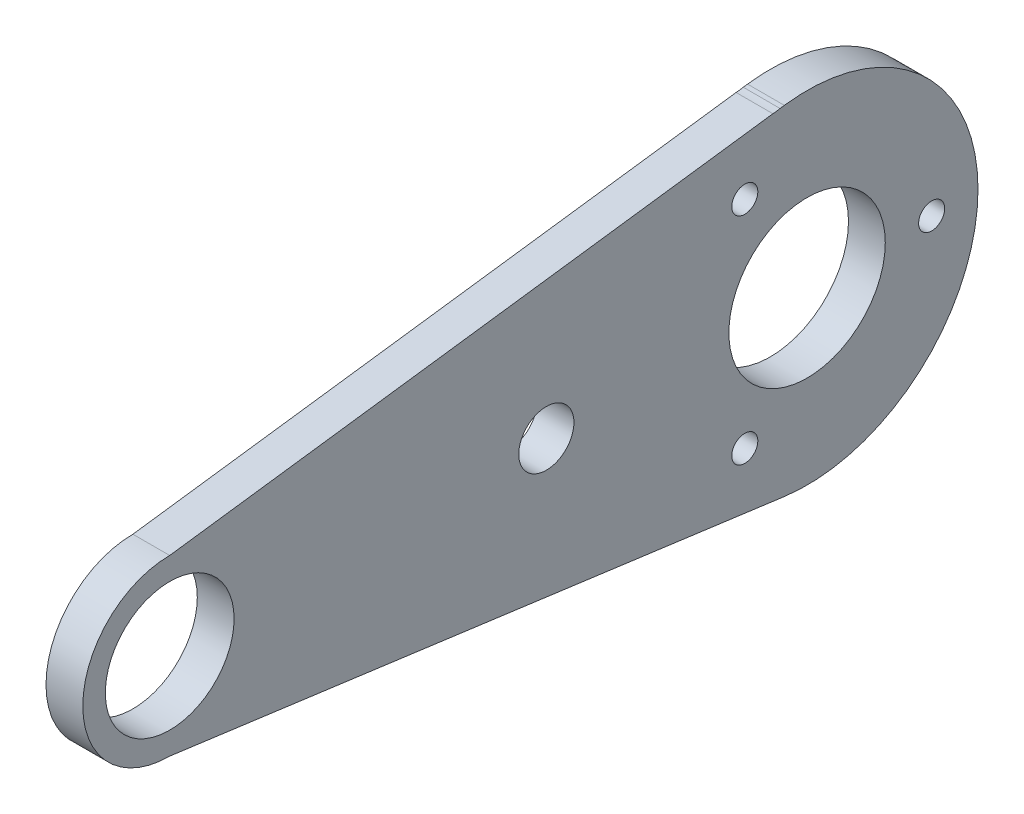
SolidWorks part; units mm, degrees
ref_plane "Front Plane" through (0, 0, 0) normal (0, 0, 1) x (1, 0, 0)
ref_plane "Top Plane" through (0, 0, 0) normal (0, 1, 0) x (1, 0, 0)
ref_plane "Right Plane" through (0, 0, 0) normal (1, 0, 0) x (0, 0, -1)
sketch "Sketch1" plane through (0, 0, 0) normal (1, 0, 0) x (0, 0, -1)
  line L4 (0, 15) -> (0, 11.1125) construction
  line L6 (0, 11.1125) -> (0, -11.1125) construction
  line L7 (0, -11.1125) -> (0, -15) construction
  line L8 (0, 15) -> (106.0756, 29.2378)
  line L9 (0, -15) -> (106.0756, -29.2378)
  line L10 (130.6993, 21.0188) -> (109.1354, 42.2549)
  line L11 (101.5842, 44.1959) -> (-4.0667, 14.4382)
  circle A0 centre (110, 0) radius 13.5
  circle A1 centre (0, 0) radius 11.1125
  arc A3 (106.0756, -29.2378) -> (106.0756, 29.2378) centre (110, 0) ccw
  arc A5 (0, 15) -> (0, -15) centre (0, 0) ccw
  arc A6 (106.0756, 29.2378) -> (106.0756, -29.2378) centre (110, 0) ccw construction
  arc A7 (0, -15) -> (0, 15) centre (0, 0) ccw construction
  circle A8 centre (0, 0) radius 110 construction
  circle A9 centre (0, 0) radius 100 construction
  circle A10 centre (103.6887, 36.7241) radius 4.7625
  circle A11 centre (103.6887, 36.7241) radius 7.7625
  dimension "D3" = 22.225
  dimension "D4" = 9.525
  dimension "D5" = 27
  dimension "D6" = 59
  dimension "D7" = 3
  dimension "D1" = 10
  dimension "D2" = 110
  dimension "D9" = 30
extrude "Boss-Extrude1" add sketch "Sketch1" along normal mid plane 6.35 contours A11 L8 A5 L9 A3 A0 A1
hole_wizard "M4 Clearance Hole1" positions "Sketch2" profile "Sketch3" hole size "M4" standard "ANSI Metric" end condition through all
sketch "Sketch2" plane through (3.175, 0, 0) normal (1, 0, 0) x (0, 0, -1)
  line L0 (110, 0) -> (131.5, 0) construction
  line L1 (110, 0) -> (99.25, -18.6195) construction
  line L2 (110, 0) -> (99.25, 18.6195) construction
  point P2 (131.5, 0)
  point P12 (99.25, -18.6195)
  point P13 (99.25, 18.6195)
  dimension "D1" = 21.5
  dimension "D2" = 3
sketch "Sketch3" plane through (3.175, 18.6195, -99.25) normal (0, 1, 0) x (0, 0, -1)
  line L0 (0, 0) -> (0, 6.35)
  line L1 (0, 6.35) -> (2.25, 6.35)
  line L2 (2.25, 6.35) -> (2.25, 0)
  line L5 (2.25, 0) -> (0, 0)
  line L11 (0, -6.35) -> (0, 107.95) construction
  dimension "Thru Hole Dia." = 4.5
  dimension "Thru Hole Depth" = 6.35
hole_wizard "3/8 (0.3750) Dowel Hole1" positions "Sketch4" profile "Sketch5" hole size "3/8" standard "ANSI Inch" end condition through all
sketch "Sketch4" plane through (3.175, 0, 0) normal (1, 0, 0) x (0, 0, -1)
  point P0 (65, 0)
  dimension "D1" = 65
sketch "Sketch5" plane through (3.175, 0, -65) normal (0, 1, 0) x (0, 0, -1)
  line L0 (0, 0) -> (0, 6.35)
  line L1 (0, 6.35) -> (4.7625, 6.35)
  line L2 (4.7625, 6.35) -> (4.7625, 0)
  line L5 (4.7625, 0) -> (0, 0)
  line L11 (0, -6.35) -> (0, 107.95) construction
  dimension "Thru Hole Dia." = 9.525
  dimension "Thru Hole Depth" = 6.35
